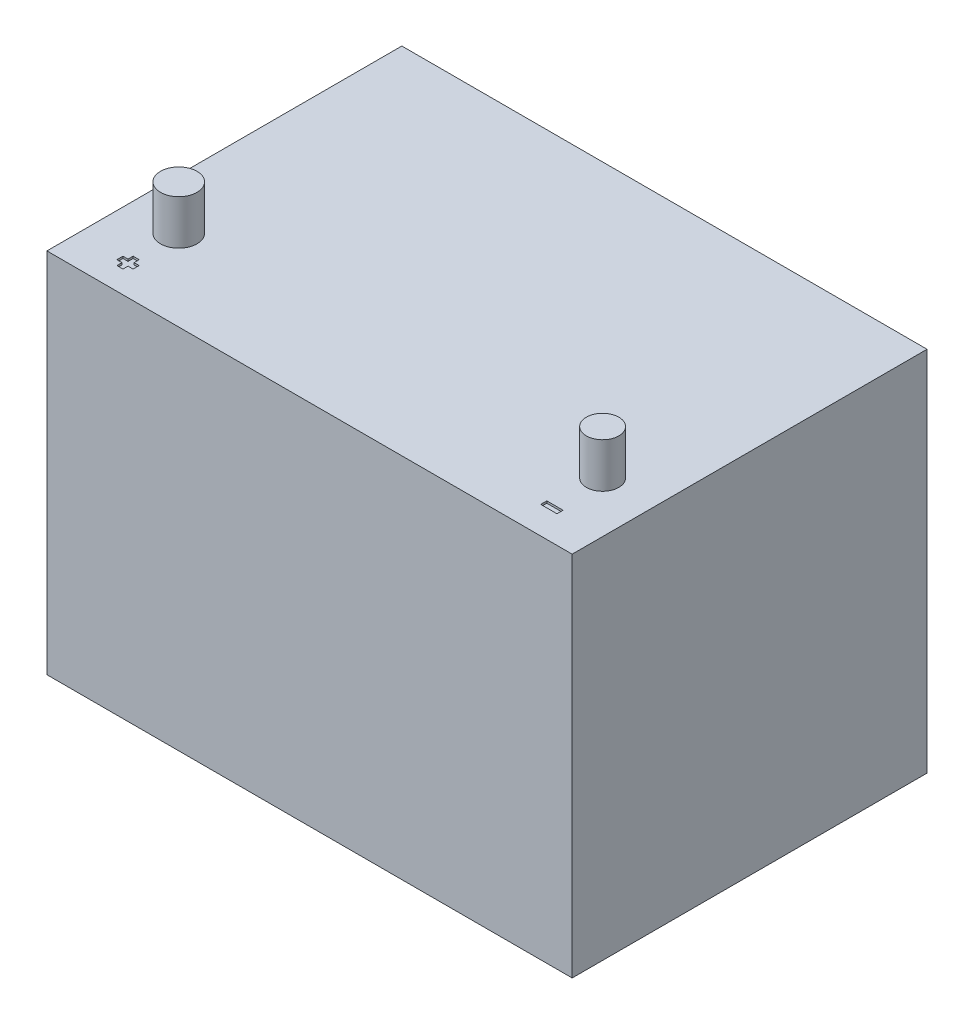
SolidWorks part; units mm, degrees
ref_plane "Front Plane" through (0, 0, 0) normal (0, 0, 1) x (1, 0, 0)
ref_plane "Top Plane" through (0, 0, 0) normal (0, 1, 0) x (1, 0, 0)
ref_plane "Right Plane" through (0, 0, 0) normal (1, 0, 0) x (0, 0, -1)
sketch "Sketch1" plane through (0, 0, 0) normal (0, 1, 0) x (1, 0, 0)
  line L1 (-129.5, 87.5) -> (129.5, 87.5)
  line L2 (-129.5, 87.5) -> (-129.5, -87.5)
  line L3 (-129.5, -87.5) -> (129.5, -87.5)
  line L4 (129.5, 87.5) -> (129.5, -87.5)
  line L5 (-129.5, 87.5) -> (129.5, -87.5) construction
  line L6 (-129.5, -87.5) -> (129.5, 87.5) construction
  point P0 (0, 0)
  dimension "D1" = 259
  dimension "D2" = 175
extrude "Boss-Extrude1" add sketch "Sketch1" along normal blind 181
sketch "Sketch2" plane through (0, 181, 0) normal (0, 1, 0) x (1, 0, 0)
  line L0 (129.5, -87.5) -> (129.5, 87.5) construction
  line L3 (-129.5, -87.5) -> (129.5, -87.5) construction
  circle A0 centre (-104.5, -47.5) radius 9
  circle A1 centre (104.5, -47.5) radius 8
  point P4 (-104.5, -47.5)
  point P7 (104.5, -47.5)
  dimension "D3" = 18
  dimension "D5" = 16
  dimension "D1" = 25
  dimension "D2" = 209
  dimension "D4" = 40
extrude "Boss-Extrude2" add sketch "Sketch2" along normal blind 22
sketch "Sketch3" plane through (0, 181, 0) normal (0, 1, 0) x (1, 0, 0)
  line L0 (-129.5, 87.5) -> (-129.5, -87.5) construction
  line L1 (-106, -68.5) -> (-103, -68.5)
  line L2 (-106, -68.5) -> (-106, -76.5)
  line L3 (-106, -76.5) -> (-103, -76.5)
  line L4 (-103, -68.5) -> (-103, -76.5)
  line L5 (-106, -68.5) -> (-103, -76.5) construction
  line L6 (-106, -76.5) -> (-103, -68.5) construction
  line L7 (-108.5, -71) -> (-100.5, -71)
  line L8 (-108.5, -71) -> (-108.5, -74)
  line L9 (-108.5, -74) -> (-100.5, -74)
  line L10 (-100.5, -71) -> (-100.5, -74)
  line L11 (-108.5, -71) -> (-100.5, -74) construction
  line L12 (-108.5, -74) -> (-100.5, -71) construction
  line L13 (-129.5, -87.5) -> (129.5, -87.5) construction
  line L14 (129.5, -87.5) -> (129.5, 87.5) construction
  line L15 (100.5, -74) -> (108.5, -74)
  line L16 (100.5, -74) -> (100.5, -71)
  line L17 (100.5, -71) -> (108.5, -71)
  line L18 (108.5, -74) -> (108.5, -71)
  line L19 (100.5, -74) -> (108.5, -71) construction
  line L20 (100.5, -71) -> (108.5, -74) construction
  point P4 (-104.5, -72.5)
  point P9 (-104.5, -72.5)
  point P19 (104.5, -72.5)
  dimension "D1" = 8
  dimension "D2" = 8
  dimension "D3" = 25
  dimension "D4" = 15
  dimension "D5" = 3
  dimension "D6" = 3
  dimension "D7" = 25
  dimension "D8" = 3
  dimension "D9" = 8
  dimension "D10" = 15
extrude "Cut-Extrude1" cut sketch "Sketch3" against normal blind 1 contours L8 L9 L2 L7 | L2 L9 L4 L7 | L2 L7 L4 L1 | L10 L7 L4 L9 | L9 L2 L3 L4 | L15 L18 L17 L16
